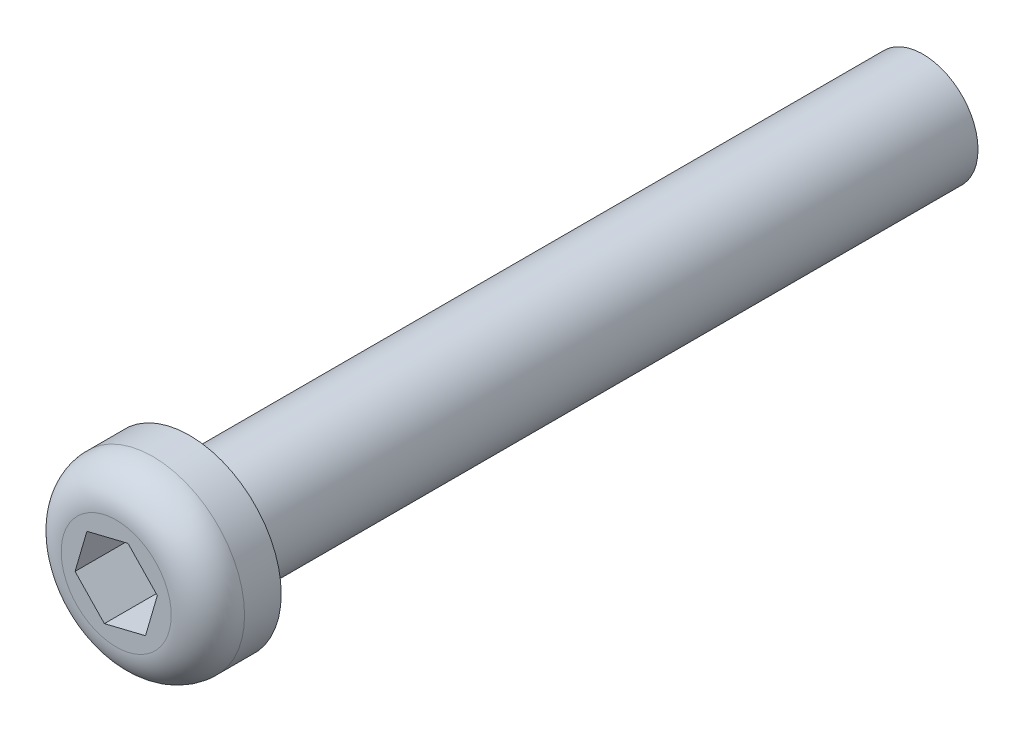
SolidWorks part; units mm, degrees
ref_plane "前视基准面" through (0, 0, 0) normal (0, 0, 1) x (1, 0, 0)
ref_plane "上视基准面" through (0, 0, 0) normal (0, 1, 0) x (1, 0, 0)
ref_plane "右视基准面" through (0, 0, 0) normal (1, 0, 0) x (0, 0, -1)
sketch "草图1" plane through (0, 0, 0) normal (0, 0, 1) x (1, 0, 0)
  circle A0 centre (0, 0) radius 1.5
  dimension "D1" = 3
extrude "凸台-拉伸1" add sketch "草图1" along normal blind 20
sketch "草图2" plane through (0, 0, 20) normal (0, 0, 1) x (1, 0, 0)
  circle A0 centre (0, 0) radius 2.5
  dimension "D1" = 5
extrude "凸台-拉伸2" add sketch "草图2" along normal blind 2
sketch "草图3" plane through (0, 0, 22) normal (0, 0, 1) x (1, 0, 0)
  line L1 (0.3225, 1.1087) -> (-0.7989, 0.8337)
  line L2 (-0.7989, 0.8337) -> (-1.1215, -0.275)
  line L3 (-1.1215, -0.275) -> (-0.3225, -1.1087)
  line L4 (-0.3225, -1.1087) -> (0.7989, -0.8337)
  line L5 (0.7989, -0.8337) -> (1.1215, 0.275)
  line L6 (1.1215, 0.275) -> (0.3225, 1.1087)
  circle A0 centre (0, 0) radius 1 construction
  dimension "D1" = 2
extrude "切除-拉伸1" cut sketch "草图3" against normal blind 1.5
fillet "圆角1" radius 1 1 edges at (2.5, 0, 22)
